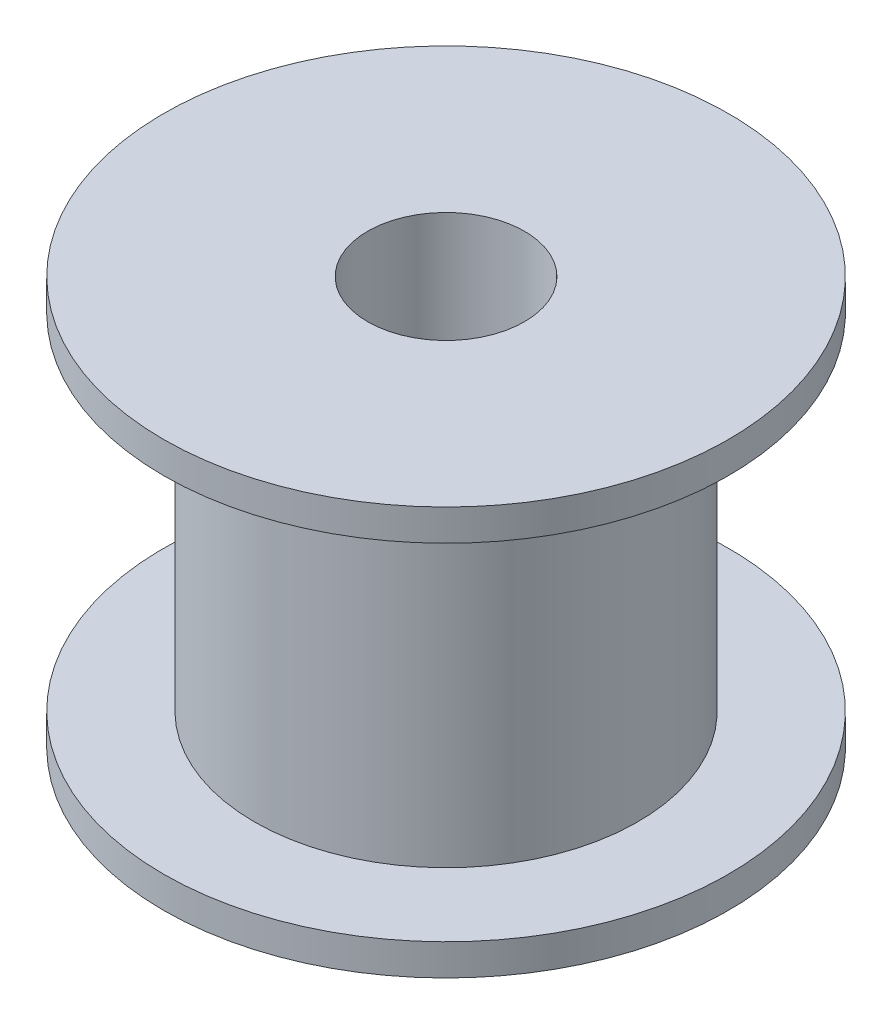
SolidWorks part; units mm, degrees
material "1060 合金"
ref_plane "前视基准面" through (0, 0, 0) normal (0, 0, 1) x (1, 0, 0)
ref_plane "上视基准面" through (0, 0, 0) normal (0, 1, 0) x (1, 0, 0)
ref_plane "右视基准面" through (0, 0, 0) normal (1, 0, 0) x (0, 0, -1)
other "Configuration Table"
sketch "草图1" plane through (0, 0, 0) normal (0, 1, 0) x (1, 0, 0)
  circle A0 centre (0, 0) radius 9
  dimension "D1" = 18
extrude "凸台-拉伸1" add sketch "草图1" along normal blind 1
sketch "草图2" plane through (0, 1, 0) normal (0, 1, 0) x (1, 0, 0)
  circle A0 centre (0, 0) radius 6.11
  dimension "D1" = 12.22
extrude "凸台-拉伸2" add sketch "草图2" along normal blind 11
sketch "草图3" plane through (0, 12, 0) normal (0, 1, 0) x (1, 0, 0)
  circle A0 centre (0, 0) radius 9
  dimension "D1" = 18
extrude "凸台-拉伸3" add sketch "草图3" along normal blind 1
sketch "草图4" plane through (0, 13, 0) normal (0, 1, 0) x (1, 0, 0)
  circle A0 centre (0, 0) radius 2.5
  dimension "D1" = 5
extrude "切除-拉伸1" cut sketch "草图4" against normal blind 13
